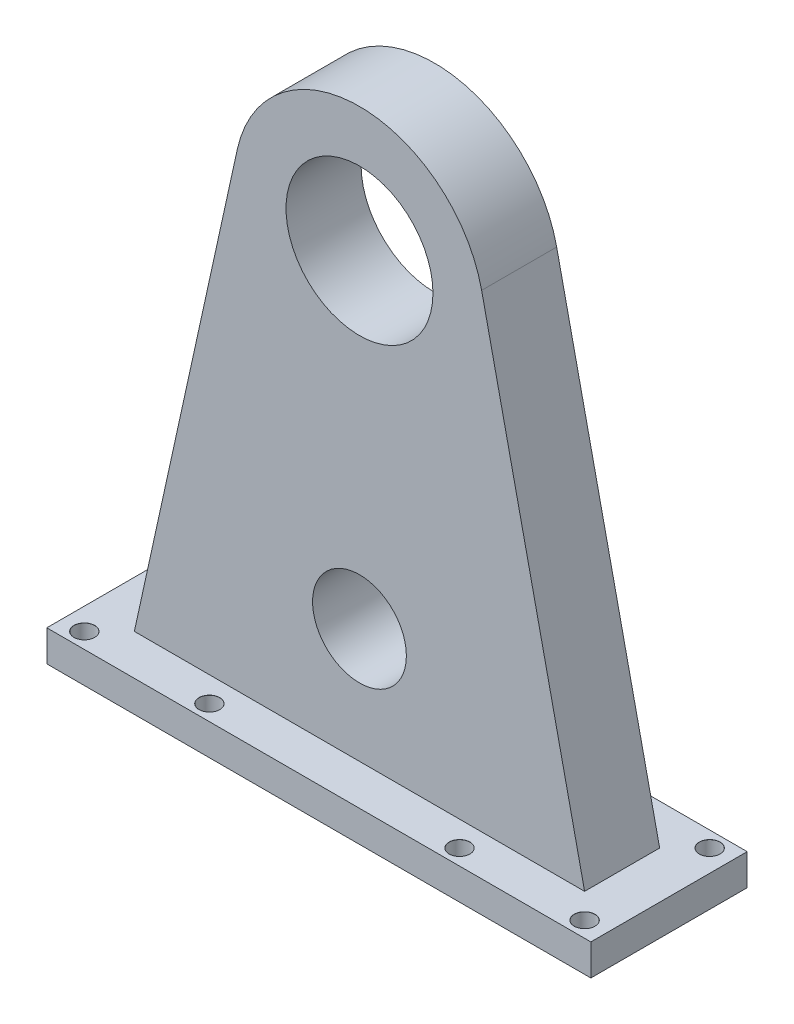
SolidWorks part; units mm, degrees
ref_plane "Front Plane" through (0, 0, 0) normal (0, 0, 1) x (1, 0, 0)
ref_plane "Top Plane" through (0, 0, 0) normal (0, 1, 0) x (1, 0, 0)
ref_plane "Right Plane" through (0, 0, 0) normal (1, 0, 0) x (0, 0, -1)
sketch "Sketch1" plane through (0, 0, 0) normal (0, 1, 0) x (1, 0, 0)
  line L1 (-87, 25) -> (87, 25)
  line L2 (-87, 25) -> (-87, -25)
  line L3 (-87, -25) -> (87, -25)
  line L4 (87, 25) -> (87, -25)
  line L5 (-87, 25) -> (87, -25) construction
  line L6 (-87, -25) -> (87, 25) construction
  point P0 (0, 0)
  dimension "D1" = 174
  dimension "D2" = 50
extrude "Boss-Extrude1" add sketch "Sketch1" along normal blind 10
hole_wizard "M6 Clearance Hole1" positions "Sketch4" profile "Sketch5" hole size "M6" standard "ANSI Metric" end condition up to next
sketch "Sketch4" plane through (0, 10, 0) normal (0, 1, 0) x (1, 0, 0)
  line L0 (-80, 20) -> (-40, 20) construction
  line L1 (-40, 20) -> (40, 20) construction
  line L2 (40, 20) -> (80, 20) construction
  line L4 (-80, 20) -> (-80, -20) construction
  line L6 (80, 20) -> (80, -20) construction
  point P0 (-80, 20)
  point P2 (-40, 20)
  point P4 (-80, -20)
  point P6 (-40, -20)
  point P8 (40, 20)
  point P10 (80, 20)
  point P12 (40, -20)
  point P14 (80, -20)
  point P39 (-80, 0)
  point P41 (0, 20)
  dimension "D1" = 40
  dimension "D2" = 40
  dimension "D3" = 80
sketch "Sketch5" plane through (-80, 10, -20) normal (1, 0, 0) x (0, 0, 1)
  line L0 (0, 0) -> (0, 10)
  line L1 (0, 10) -> (3.3, 10)
  line L2 (3.3, 10) -> (3.3, 0.021)
  line L3 (3.3, 0.021) -> (3.325, 0)
  line L5 (3.325, 0) -> (0, 0)
  line L6 (-3.3, 0.021) -> (-3.325, 0) construction
  line L11 (0, -6.35) -> (0, 107.95) construction
  dimension "Thru Hole Dia." = 6.6
  dimension "Thru Hole Depth" = 10
  dimension "Near C'Sink Dia." = 6.65
  dimension "Near C'Sink Angle" = 100
sketch "Sketch6" plane through (0, 0, 0) normal (0, 0, 1) x (1, 0, 0)
  line L0 (-72, 10) -> (72, 10)
  line L1 (-87, 10) -> (87, 10) construction
  line L2 (72, 10) -> (39.0696, 160)
  line L4 (-39.0696, 160) -> (-72, 10)
  line L5 (87, 10) -> (87, 0) construction
  line L6 (-87, 10) -> (-87, 0) construction
  arc A0 (-39.0696, 160) -> (39.0696, 160) centre (0, 151.4228) cw
  point P12 (0, 10)
  dimension "D4" = 40
  dimension "D1" = 15
  dimension "D2" = 15
  dimension "D3" = 150
extrude "Boss-Extrude2" add sketch "Sketch6" along normal blind 12 and the other way blind 12
sketch "Sketch7" plane through (0, 0, 12) normal (0, 0, 1) x (1, 0, 0)
  circle A2 centre (0, 46.7228) radius 15
  circle A3 centre (0, 151.4228) radius 23.5
  arc A4 (39.0696, 160) -> (-39.0696, 160) centre (0, 151.4228) ccw construction
  point P4 (0, 0)
  point P5 (0, 0)
  point P9 (0, 0)
  dimension "D3" = 104.7
  dimension "D1" = 30
  dimension "D2" = 47
extrude "Cut-Extrude1" cut sketch "Sketch7" against normal up to next
